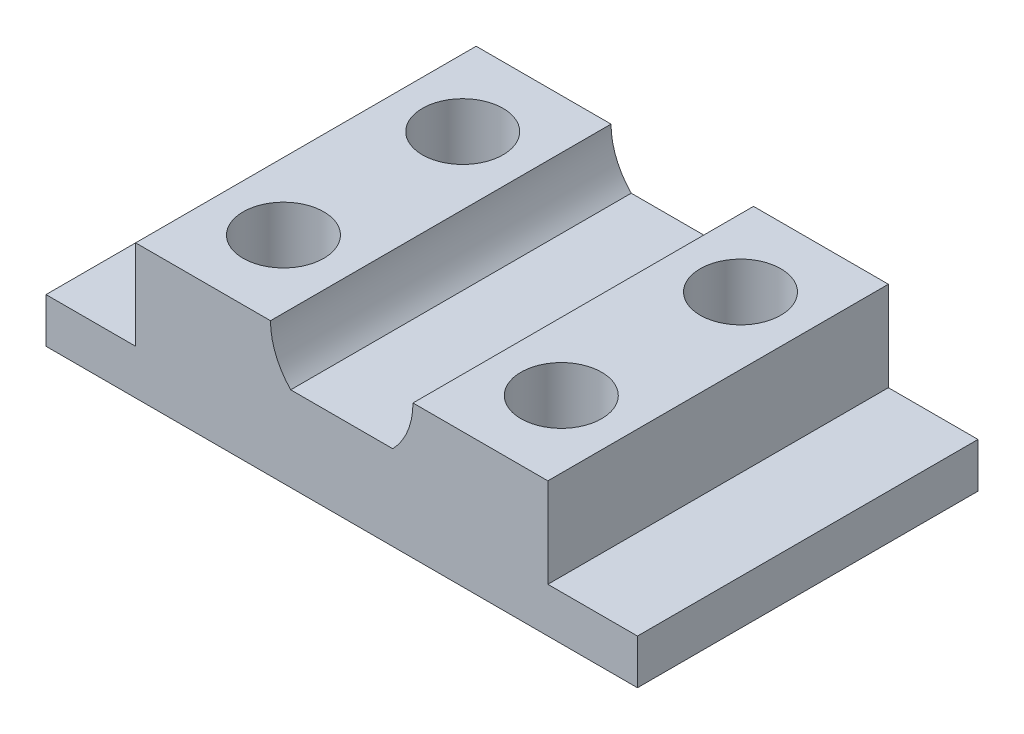
SolidWorks part; units mm, degrees
ref_plane "Front Plane" through (0, 0, 0) normal (0, 0, 1) x (1, 0, 0)
ref_plane "Top Plane" through (0, 0, 0) normal (0, 1, 0) x (1, 0, 0)
ref_plane "Right Plane" through (0, 0, 0) normal (1, 0, 0) x (0, 0, -1)
sketch "Sketch1" plane through (0, 0, 0) normal (0, 1, 0) x (1, 0, 0)
  line L1 (0, 0) -> (46, 0)
  line L2 (0, 0) -> (0, 38)
  line L3 (0, 38) -> (46, 38)
  line L4 (46, 0) -> (46, 38)
  dimension "D1" = 46
  dimension "D2" = 38
extrude "Boss-Extrude1" add sketch "Sketch1" along normal blind 15
ref_plane "Plane4" through (23, 0, 0) normal (1, 0, 0) x (0, 0, -1)
sketch "Sketch4" plane through (0, 15, 0) normal (0, 1, 0) x (1, 0, 0)
  line L0 (0, 38) -> (0, 0) construction
  line L1 (7.5, 29) -> (38.5, 29)
  line L2 (7.5, 29) -> (7.5, 9)
  line L3 (7.5, 9) -> (38.5, 9)
  line L4 (38.5, 29) -> (38.5, 9)
  line L7 (46, 0) -> (46, 38) construction
  line L8 (0, 0) -> (46, 0) construction
  line L9 (13.2102, 9) -> (13.2102, 0) construction
  line L10 (13.2102, 38) -> (13.2102, 29) construction
  line L11 (46, 38) -> (0, 38) construction
  dimension "D1" = 7.5
  dimension "D2" = 20
  dimension "D4" = 7.5
hole_wizard "M10x1.0 Tapped Hole1" positions "Sketch5" profile "Sketch6" tap size "M10x1.0" standard "ANSI Metric" end condition through all
sketch "Sketch5" plane through (0, 15, 0) normal (0, 1, 0) x (1, 0, 0)
  point P0 (7.5, 29)
  point P3 (38.5, 29)
  point P6 (38.5, 9)
  point P9 (7.5, 9)
sketch "Sketch6" plane through (7.5, 15, -29) normal (1, 0, 0) x (0, 0, 1)
  line L0 (0, 0) -> (0, 15)
  line L1 (0, 15) -> (4.5, 15)
  line L2 (4.5, 15) -> (4.5, 0)
  line L5 (4.5, 0) -> (0, 0)
  line L11 (0, -6.35) -> (0, 107.95) construction
  dimension "Thru Tap Drill Dia." = 9
  dimension "Thru Tap Drill Depth" = 15
sketch "Sketch7" plane through (0, 0, 0) normal (0, 0, 1) x (1, 0, 0)
  line L0 (0, 15) -> (46, 15) construction
  circle A0 centre (23, 15) radius 7.95
  point P0 (0, 0)
  dimension "D2" = 15.9
extrude "Cut-Extrude1" cut sketch "Sketch7" against normal through all
sketch "Sketch17" plane through (46, 0, 0) normal (1, 0, 0) x (0, 0, -1)
  line L0 (38, 15) -> (38, 0) construction
  line L1 (0, 0) -> (38, 0)
  line L2 (0, 0) -> (0, 5)
  line L3 (0, 5) -> (38, 5)
  line L4 (38, 0) -> (38, 5)
  dimension "D1" = 5
extrude "Boss-Extrude2" add sketch "Sketch17" along normal blind 10
sketch "Sketch18" plane through (0, 0, 0) normal (-1, 0, 0) x (0, 0, 1)
  line L0 (0, 15) -> (0, 0) construction
  line L1 (-38, 0) -> (0, 0)
  line L2 (-38, 0) -> (-38, 5)
  line L3 (-38, 5) -> (0, 5)
  line L4 (0, 0) -> (0, 5)
  dimension "D1" = 5
extrude "Boss-Extrude3" add sketch "Sketch18" along normal blind 10
sketch "Sketch19" plane through (0, 5, 0) normal (0, 1, 0) x (1, 0, 0)
  line L0 (51, 38) -> (51, 0) construction
  line L1 (56, 38) -> (46, 38) construction
  line L2 (56, 0) -> (46, 0) construction
  line L3 (51, 38) -> (51, 29)
  line L4 (51, 0) -> (51, 9)
  line L5 (-5, 0) -> (-5, 38) construction
  line L6 (-10, 0) -> (0, 0) construction
  line L7 (-10, 38) -> (0, 38) construction
  line L8 (-5, 38) -> (-5, 29)
  line L9 (-5, 0) -> (-5, 9)
  dimension "D1" = 9
  dimension "D2" = 9
  dimension "D3" = 9
  dimension "D4" = 9
hole_wizard "Ø5.0mm Dowel Hole1" [suppressed] positions "Sketch20" profile "Sketch21" hole size "Ø5.0" standard "ANSI Metric"
sketch "Sketch20" plane through (0, 5, 0) normal (0, 1, 0) x (1, 0, 0)
  point P0 (-5, 9)
  point P3 (-5, 29)
  point P6 (51, 9)
  point P9 (51, 29)
sketch "Sketch21" plane through (-5, 5, -9) normal (1, 0, 0) x (0, 0, 1)
  line L0 (0, 0) -> (0, 5)
  line L1 (0, 5) -> (2.5, 5)
  line L2 (2.5, 5) -> (2.5, 0)
  line L5 (2.5, 0) -> (0, 0)
  line L11 (0, -6.35) -> (0, 107.95) construction
  dimension "Thru Hole Dia." = 5
  dimension "Thru Hole Depth" = 5
ref_plane "Plane5" through (0, 5, 0) normal (0, 0, -1) x (-1, 0, 0)
ref_plane "Plane6" through (0, 0, -19) normal (0, 0, 1) x (1, 0, 0)
sketch "Sketch23" plane through (0, 0, -19) normal (0, 0, 1) x (1, 0, 0)
  line L6 (-10, 5) -> (0, 15) construction
  line L7 (0, 15) -> (0, 5) construction
  line L9 (0, 5) -> (-10, 5) construction
  line L10 (0, 15) -> (0, 5)
  line L11 (0, 5) -> (0, 15)
  line L12 (-10, 5) -> (0, 15)
  line L13 (-10, 5) -> (0, 5)
fillet "Fillet1" [suppressed] radius 10
ref_plane "Plane7" through (0, 9.45, 0) normal (0, 1, 0) x (1, 0, 0)
sketch "Sketch24" plane through (0, 9.45, 0) normal (0, 1, 0) x (1, 0, 0)
  line L0 (55, 0) -> (-55, 0) construction
  line L1 (14.1509, 0) -> (32.1808, 0)
  line L2 (14.1509, 0) -> (14.1509, 38)
  line L3 (14.1509, 38) -> (32.1808, 38)
  line L4 (32.1808, 0) -> (32.1808, 38)
  line L5 (46, 38) -> (30.95, 38) construction
extrude "Boss-Extrude4" add sketch "Sketch24" against normal blind 6
